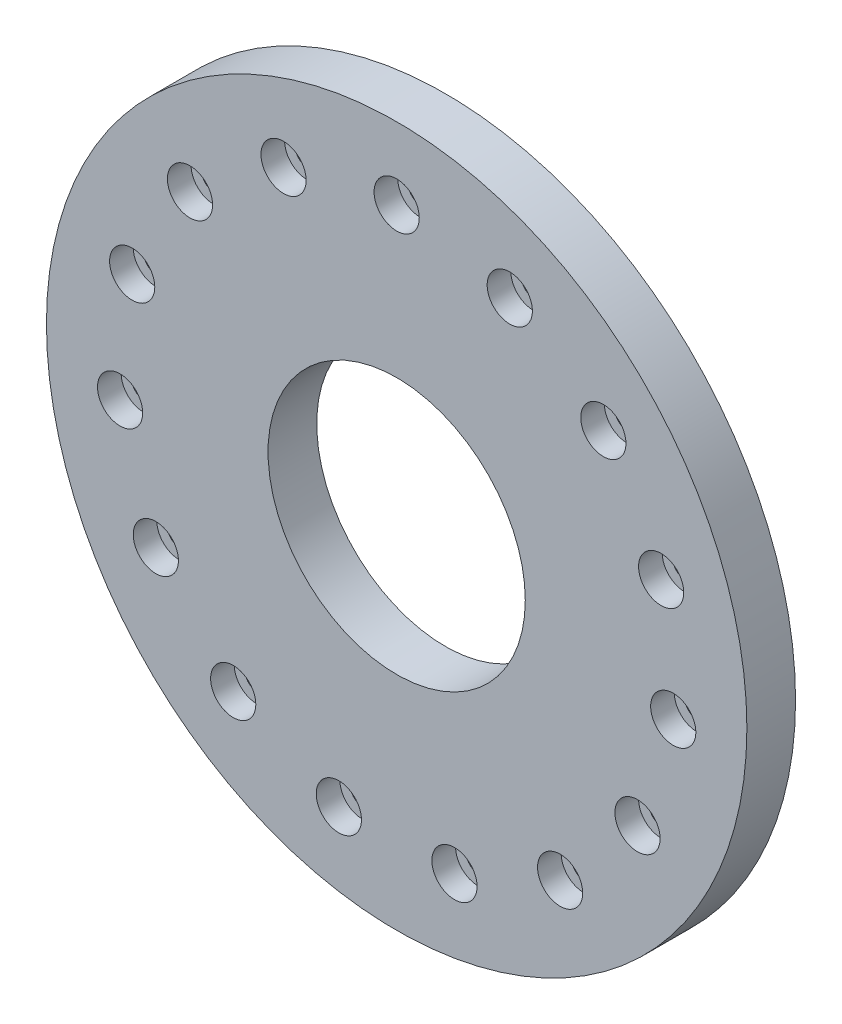
SolidWorks part; units mm, degrees
ref_plane "Front Plane" through (0, 0, 0) normal (0, 0, 1) x (1, 0, 0)
ref_plane "Top Plane" through (0, 0, 0) normal (0, 1, 0) x (1, 0, 0)
ref_plane "Right Plane" through (0, 0, 0) normal (1, 0, 0) x (0, 0, -1)
sketch "Sketch1" plane through (0, 0, 0) normal (0, 0, 1) x (1, 0, 0)
  circle A0 centre (0, 0) radius 50.375
  dimension "D1" = 100.75
extrude "Boss-Extrude1" add sketch "Sketch1" along normal blind 7 contours A0
sketch "Sketch2" plane through (0, 0, 7) normal (0, 0, 1) x (1, 0, 0)
  circle A0 centre (0, 40) radius 3
  circle A1 centre (16.2695, 36.5418) radius 3
  circle A2 centre (29.7258, 26.7652) radius 3
  circle A3 centre (38.0423, 12.3607) radius 3
  circle A4 centre (39.7809, -4.1811) radius 3
  circle A5 centre (34.641, -20) radius 3
  circle A6 centre (23.5114, -32.3607) radius 3
  circle A7 centre (8.3165, -39.1259) radius 3
  circle A8 centre (-8.3165, -39.1259) radius 3
  circle A9 centre (-23.5114, -32.3607) radius 3
  circle A10 centre (-34.641, -20) radius 3
  circle A11 centre (-39.7809, -4.1811) radius 3
  circle A12 centre (-38.0423, 12.3607) radius 3
  circle A13 centre (-29.7258, 26.7652) radius 3
  circle A14 centre (-16.2695, 36.5418) radius 3
  point P33 (0, 0)
  dimension "D2" = 6
  dimension "D1" = 40
  dimension "D3" = 15
extrude "Cut-Extrude1" [suppressed] cut sketch "Sketch2" against normal blind 5 contours A13
sketch "Sketch3" plane through (0, 0, 7) normal (0, 0, 1) x (1, 0, 0)
  circle A0 centre (0, 0) radius 18.5
  dimension "D1" = 37
extrude "Cut-Extrude2" cut sketch "Sketch3" against normal through all
hole_wizard "CBORE for M3 Hex Socket Head Cap Screw1" positions "Sketch4" profile "Sketch6" counterbore size "M3" standard "ISO" end condition up to next
sketch "Sketch4" plane through (0, 0, 7) normal (0, 0, 1) x (1, 0, 0)
  point P0 (0, 40)
  dimension "D1" = 40
sketch "Sketch6" plane through (0, 40, 7) normal (1, 0, 0) x (0, -1, 0)
  line L0 (0, 0) -> (0, 7)
  line L1 (0, 7) -> (1.7, 7)
  line L3 (1.7, 7) -> (1.7, 3.4)
  line L4 (1.7, 3.4) -> (3.25, 3.4)
  line L5 (3.25, 3.4) -> (3.25, 0)
  line L7 (3.25, 0) -> (0, 0)
  line L11 (0, -6.35) -> (0, 107.95) construction
  dimension "Thru Hole Dia." = 3.4
  dimension "Thru Hole Depth" = 7
  dimension "C'Bore Dia." = 6.5
  dimension "C'Bore Depth" = 3.4
pattern_circular "CirPattern1" count 15 over 360 about axis through (0, 0, 0) along (0, 0, 1) of "CBORE for M3 Hex Socket Head Cap Screw1"
equation "\"roller_radius\"= 6.5"
equation "\"eccentricity\"= \"roller_radius\" * 0.325"
equation "\"outer_radius\"= 40"
equation "\"eccentric_shaft_radius\"= 16"
equation "\"rotor_width\"= 10"
equation "\"housing_depth\"= 40"
equation "\"bottom_depth\"= 5"
equation "\"roller_bearing_OD\"= \"roller_radius\" * 2"
equation "\"roller_bearing_ID\"= 6"
equation "\"eccentric_bearing_ID\"= 6"
equation "\"eccentric_bearing_OD\"= 15"
equation "\"roller_bearing_height\"= 5"
equation "\"eccentric_bearing_height\"= 5"
equation "\"bottom_bearing_ID\"= 15"
equation "\"bottom_bearing_OD\"= 32"
equation "\"bottom_bearing_height\"= 9"
equation "\"distance_to_output_rotor_holes\"= 20"
equation "\"D1@Sketch1\"=\"outer_radius\"*2+\"roller_bearing_OD\"*0.75+5.5*2"
equation "\"D1@Sketch2\"=\"outer_radius\""
equation "\"D2@Sketch2\"=\"roller_bearing_ID\""
equation "\"D1@Sketch3\"=\"output_bearing_OD\""
equation "\"D1@Sketch4\"=\"outer_radius\""
equation "\"output_bearing_ID\" = 25"
equation "\"output_bearing_OD\" = 37"
equation "\"output_bearing_height\" = 7"
equation "\"D1@Boss-Extrude1\"=\"output_bearing_height\""
